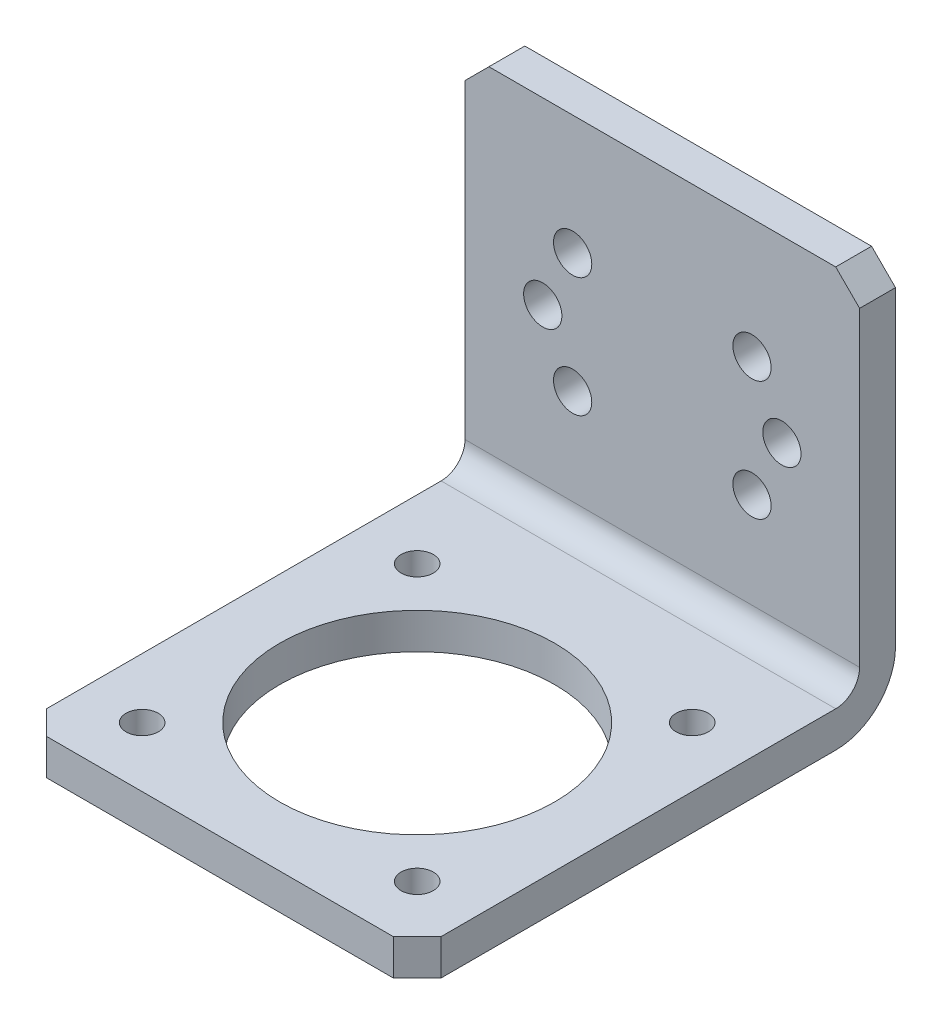
SolidWorks part; units mm, degrees
ref_plane "前视基准面" through (0, 0, 0) normal (0, 0, 1) x (1, 0, 0)
ref_plane "上视基准面" through (0, 0, 0) normal (0, 1, 0) x (1, 0, 0)
ref_plane "右视基准面" through (0, 0, 0) normal (1, 0, 0) x (0, 0, -1)
sketch "草图5" plane through (0, 0, 0) normal (0, 1, 0) x (1, 0, 0)
  line L0 (16.5, 23.5) -> (16.5, -14.5)
  line L1 (14.5, -16.5) -> (-14.5, -16.5)
  line L2 (-16.5, -14.5) -> (-16.5, 23.5)
  line L3 (-16.5, 23.5) -> (16.5, 23.5)
  line L4 (-14.5, -16.5) -> (-16.5, -14.5)
  line L5 (16.5, -14.5) -> (14.5, -16.5)
  circle A0 centre (0, 0) radius 11.5
  circle A1 centre (-11.5, -11.5) radius 1.35
  circle A2 centre (-11.5, 11.5) radius 1.35
  circle A3 centre (11.5, 11.5) radius 1.35
  circle A4 centre (11.5, -11.5) radius 1.35
  point P1 (16.5, -16.5)
  point P3 (-16.5, -16.5)
  point P18 (0, 0)
  dimension "D5" = 23
  dimension "D8" = 23
  dimension "D10" = 2.7
  dimension "D1" = 33
  dimension "D2" = 40
  dimension "D3" = 16.5
  dimension "D4" = 16.5
  dimension "D6" = 11.5
  dimension "D7" = 11.5
  dimension "D9" = 4
extrude "凸台-拉伸3" add sketch "草图5" along normal blind 3
sketch "草图8" plane through (0, 3, 0) normal (0, 1, 0) x (1, 0, 0)
  line L0 (-16.5, 20.5) -> (16.5, 20.5)
  line L1 (-16.5, 23.5) -> (-16.5, -14.5) construction
  line L2 (16.5, -14.5) -> (16.5, 23.5) construction
  line L3 (16.5, 23.5) -> (-16.5, 23.5) construction
  circle A1 centre (0, 0) radius 11.5
  circle A2 centre (0, 0) radius 11.5
  circle A3 centre (-11.5, -11.5) radius 1.35
  circle A4 centre (-11.5, -11.5) radius 1.35
  circle A5 centre (-11.5, 11.5) radius 1.35
  circle A6 centre (-11.5, 11.5) radius 1.35
  circle A7 centre (11.5, 11.5) radius 1.35
  circle A8 centre (11.5, 11.5) radius 1.35
  circle A9 centre (11.5, -11.5) radius 1.35
  circle A10 centre (11.5, -11.5) radius 1.35
  line M2 (16.5, 23.5) -> (-16.5, 23.5)
  line M3 (-16.5, 23.5) -> (-16.5, -14.5)
  line M7 (16.5, -14.5) -> (16.5, 23.5)
  dimension "D1" = 3
  dimension "D2" = 0
  dimension "D3" = 0
  dimension "D4" = 0
  dimension "D5" = 0
  dimension "D6" = 0
extrude "凸台-拉伸4" add sketch "草图8" along normal blind 30 contours L0 M3 M7 M2
sketch "草图10" plane through (0, 0, -20.5) normal (0, 0, 1) x (1, 0, 0)
  line L0 (-16.5, 33) -> (16.5, 33) construction
  line L5 (-7.5, 23) -> (-7.5, 13) construction
  circle A0 centre (-7.5, 23) radius 1.6
  circle A1 centre (7.5, 23) radius 1.6
  circle A2 centre (7.5, 13) radius 1.6
  circle A3 centre (-7.5, 13) radius 1.6
  circle A4 centre (-10, 18) radius 1.6
  circle A5 centre (10, 18) radius 1.6
  point P4 (-7.5, 18)
  dimension "D1" = 3.2
  dimension "D3" = 3.2
  dimension "D4" = 3.2
  dimension "D5" = 3.2
  dimension "D9" = 3.2
  dimension "D2" = 7.5
  dimension "D6" = 7.5
  dimension "D7" = 10
  dimension "D8" = 10
  dimension "D10" = 10
  dimension "D11" = 10
extrude "切除-拉伸4" cut sketch "草图10" against normal blind 5
fillet "圆角1" radius 2 1 edges at (0, 3, -20.5)
fillet "圆角2" radius 5 1 edges at (0, 0, -23.5)
chamfer "倒角1" distance 2 angle 45 2 edges at (-16.5, 33, -22) (16.5, 33, -22)
